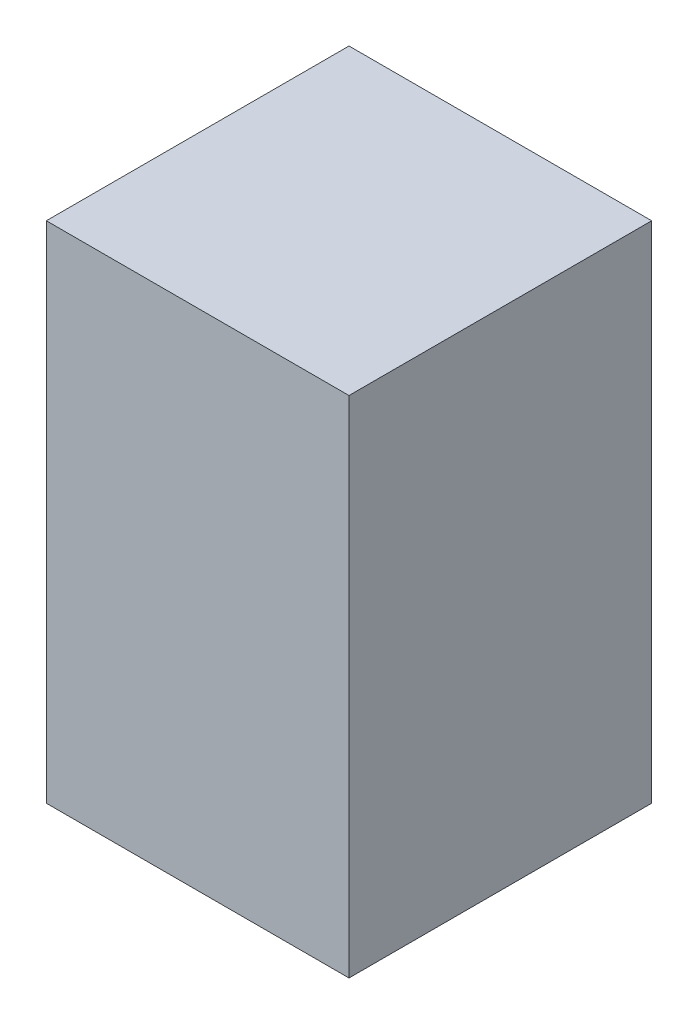
SolidWorks part; units mm, degrees
ref_plane "Front Plane" through (0, 0, 0) normal (0, 0, 1) x (1, 0, 0)
ref_plane "Top Plane" through (0, 0, 0) normal (0, 1, 0) x (1, 0, 0)
ref_plane "Right Plane" through (0, 0, 0) normal (1, 0, 0) x (0, 0, -1)
sketch "Sketch1" plane through (0, 0, 0) normal (0, 1, 0) x (1, 0, 0)
  line L2 (-6, 3.6622) -> (0, 3.6622)
  line L3 (-6, 3.6622) -> (-6, -2.3378)
  line L4 (-6, -2.3378) -> (0, -2.3378)
  line L5 (0, 3.6622) -> (0, -2.3378)
  dimension "D1" = 6
  dimension "D2" = 6
extrude "Boss-Extrude1" add sketch "Sketch1" along normal blind 10
